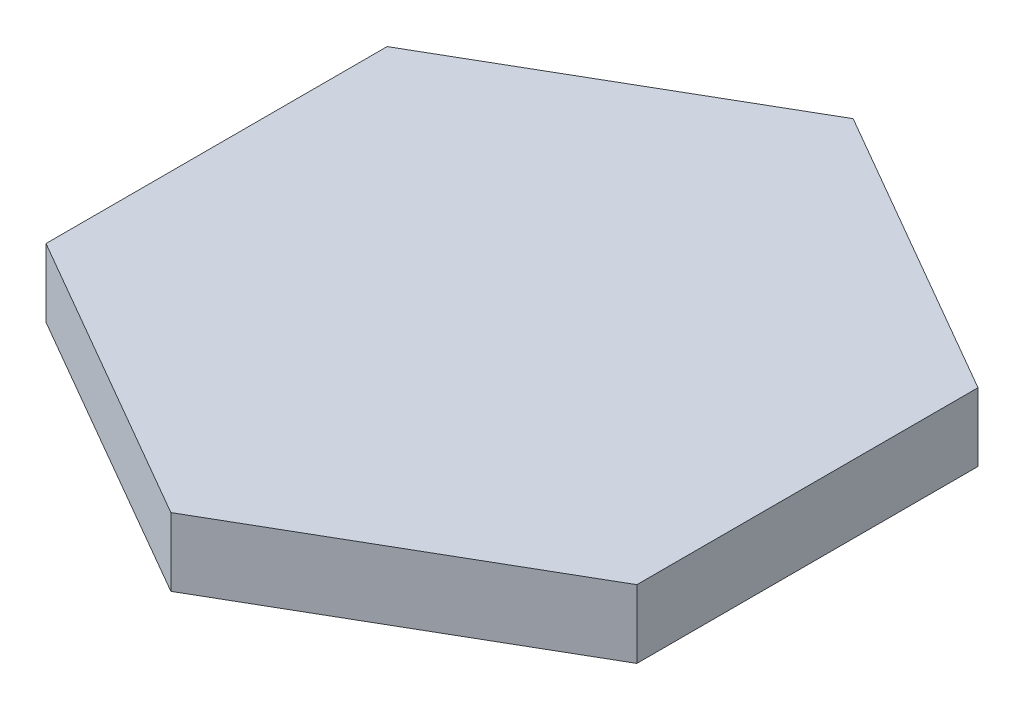
SolidWorks part; units mm, degrees
ref_plane "Plan de face" through (0, 0, 0) normal (0, 0, 1) x (1, 0, 0)
ref_plane "Plan de dessus" through (0, 0, 0) normal (0, 1, 0) x (1, 0, 0)
ref_plane "Plan de droite" through (0, 0, 0) normal (1, 0, 0) x (0, 0, -1)
sketch "Esquisse1" plane through (0, 0, 0) normal (0, 1, 0) x (1, 0, 0)
  line L7 (0, 75) -> (-64.9519, 37.5)
  line L8 (-64.9519, 37.5) -> (-64.9519, -37.5)
  line L9 (-64.9519, -37.5) -> (0, -75)
  line L10 (0, -75) -> (64.9519, -37.5)
  line L11 (64.9519, -37.5) -> (64.9519, 37.5)
  line L12 (64.9519, 37.5) -> (0, 75)
  circle A0 centre (0, 0) radius 75 construction
  dimension "D1" = 150
extrude "Boss.-Extru.1" add sketch "Esquisse1" along normal blind 15
